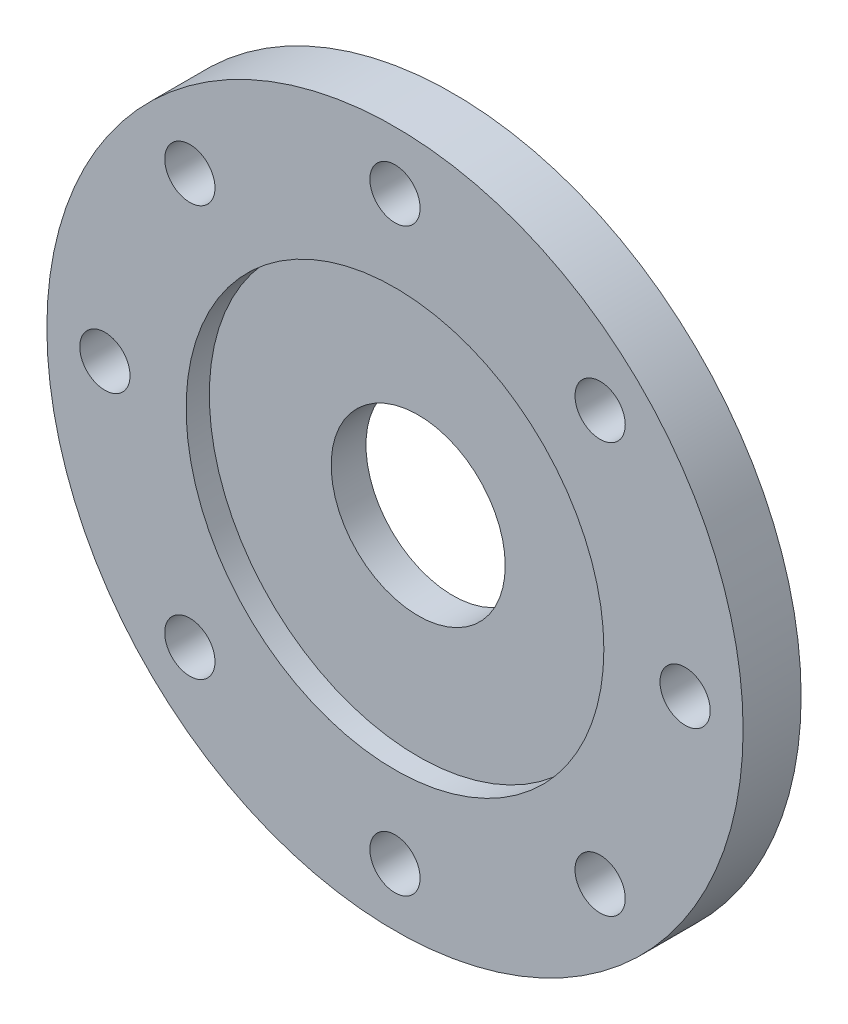
SolidWorks part; units mm, degrees
material "6061-T6 (SS)"
ref_plane "Front Plane" through (0, 0, 0) normal (0, 0, 1) x (1, 0, 0)
ref_plane "Top Plane" through (0, 0, 0) normal (0, 1, 0) x (1, 0, 0)
ref_plane "Right Plane" through (0, 0, 0) normal (1, 0, 0) x (0, 0, -1)
sketch "Sketch1" plane through (0, 0, 0) normal (0, 0, 1) x (1, 0, 0)
  circle A0 centre (0, 0) radius 15.875 construction
  circle A1 centre (0, 15.875) radius 1.375
  circle A2 centre (11.2253, 11.2253) radius 1.375
  circle A3 centre (15.875, 0) radius 1.375
  circle A4 centre (0, 0) radius 19.05
  circle A5 centre (0, 0) radius 4.7625
  circle A6 centre (11.2253, -11.2253) radius 1.375
  circle A7 centre (0, -15.875) radius 1.375
  circle A8 centre (-11.2253, -11.2253) radius 1.375
  circle A9 centre (-15.875, 0) radius 1.375
  circle A10 centre (-11.2253, 11.2253) radius 1.375
  dimension "D2" = 2.75
  dimension "D3" = 8
  dimension "D5" = 38.1
  dimension "D6" = 9.525
  dimension "D1" = 31.75
extrude "Boss-Extrude1" add sketch "Sketch1" along normal blind 3.175
sketch "Sketch2" plane through (0, 0, 3.175) normal (0, 0, 1) x (1, 0, 0)
  circle A0 centre (0, 0) radius 11.43
  dimension "D1" = 22.86
extrude "Cut-Extrude1" cut sketch "Sketch2" against normal blind 1.27
